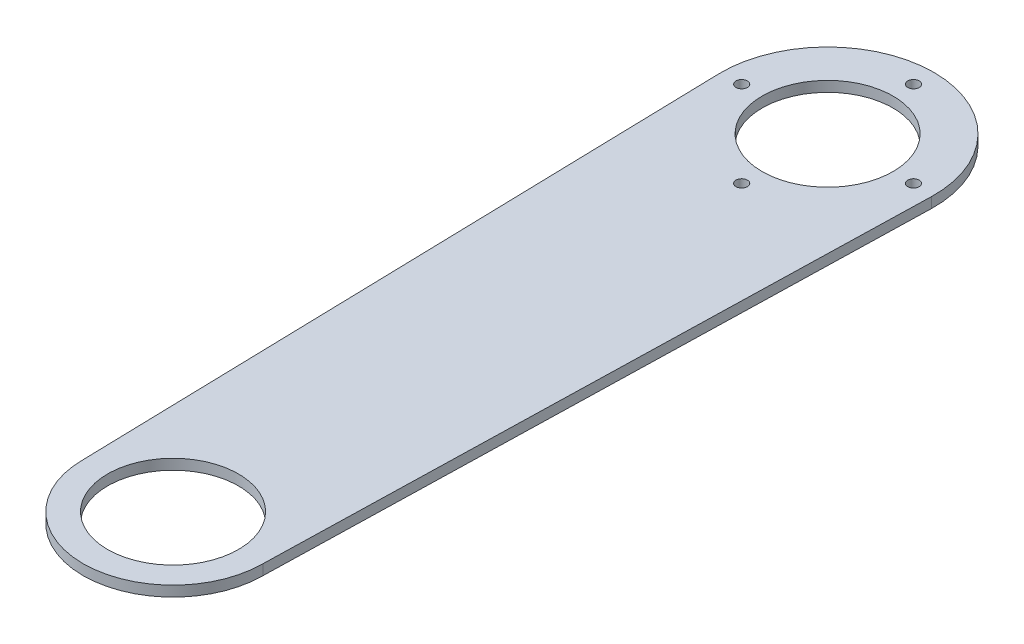
SolidWorks part; units mm, degrees
ref_plane "Front Plane" through (0, 0, 0) normal (0, 0, 1) x (1, 0, 0)
ref_plane "Top Plane" through (0, 0, 0) normal (0, 1, 0) x (1, 0, 0)
ref_plane "Right Plane" through (0, 0, 0) normal (1, 0, 0) x (0, 0, -1)
sketch "Sketch1" plane through (0, 0, 0) normal (0, 1, 0) x (1, 0, 0)
  line L0 (-27.5, -100) -> (-32.4898, 99.1861)
  line L1 (27.5, -100) -> (32.4898, 99.1861)
  arc A0 (-27.5, -100) -> (27.5, -100) centre (0, -100) ccw
  arc A2 (32.4898, 99.1861) -> (-32.4898, 99.1861) centre (0, 100) ccw
  point P1 (0, 0)
  point P8 (-18.7432, -85.6231)
  point P9 (0, 0)
  point P10 (0, 0)
  point P11 (43.9107, 196.3296)
  dimension "D1" = 55
  dimension "D2" = 200
  dimension "D3" = 65
  dimension "D4" = 100
extrude "Boss-Extrude1" add sketch "Sketch1" along normal blind 3.175
sketch "Sketch2" plane through (0, 3.175, 0) normal (0, 1, 0) x (1, 0, 0)
  circle A0 centre (0, -100) radius 20
  circle A1 centre (0, 100) radius 20
  point P3 (0, 0)
  point P4 (10.7175, -100)
  dimension "D1" = 40
  dimension "D2" = 200
  dimension "D3" = 100
extrude "Cut-Extrude1" cut sketch "Sketch2" against normal through all
sketch "Esquisse1" plane through (0, 3.175, 0) normal (0, 1, 0) x (1, 0, 0)
  circle A0 centre (0, 100) radius 26.25
  circle A2 centre (0, 100) radius 20 construction
  dimension "D1" = 52.5
sketch "Esquisse2" plane through (0, 3.175, 0) normal (0, 1, 0) x (1, 0, 0)
  circle A0 centre (0, 73.75) radius 1.75
  circle A1 centre (0, 100) radius 26.25 construction
  circle A2 centre (26.25, 100) radius 1.75
  circle A3 centre (0, 126.25) radius 1.75
  circle A4 centre (-26.25, 100) radius 1.75
  point P10 (0, 0)
  point P12 (0, 0)
  point P14 (3.848, 74.0336)
  dimension "D1" = 3.5
extrude "Enlèv. mat.-Extru.1" cut sketch "Esquisse2" against normal through all
